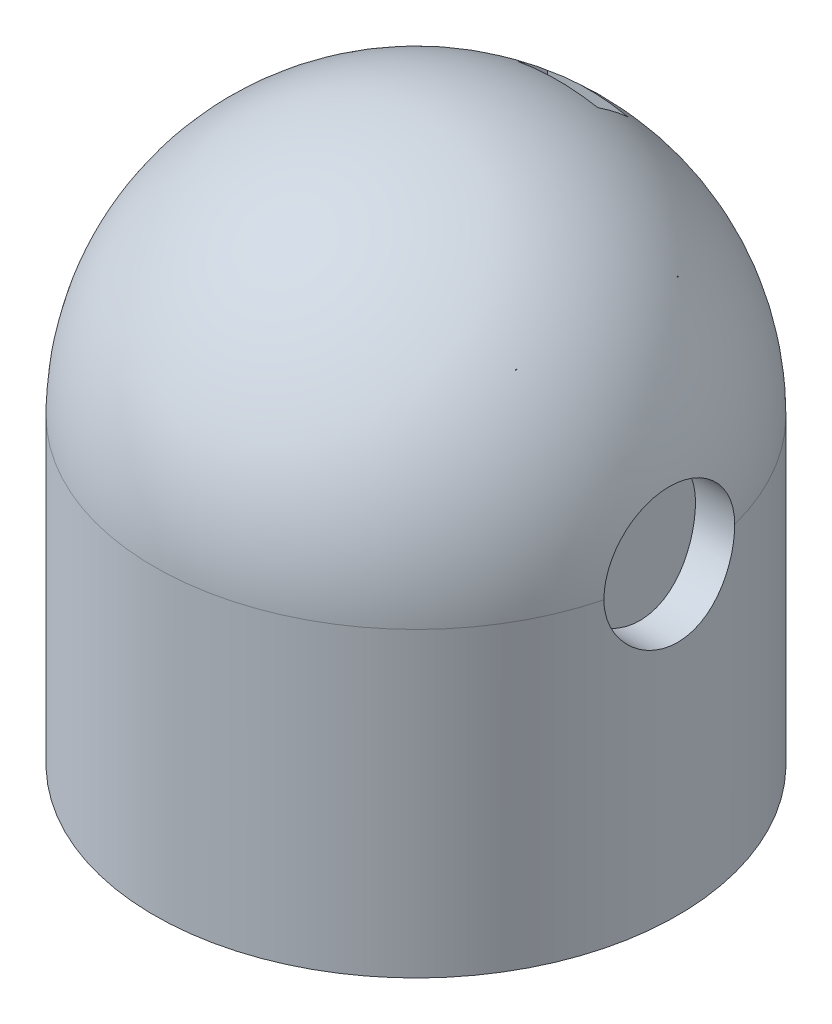
SolidWorks part; units mm, degrees
ref_plane "Front Plane" through (0, 0, 0) normal (0, 0, 1) x (1, 0, 0)
ref_plane "Top Plane" through (0, 0, 0) normal (0, 1, 0) x (1, 0, 0)
ref_plane "Right Plane" through (0, 0, 0) normal (1, 0, 0) x (0, 0, -1)
sketch "Sketch2" plane through (0, 0, 0) normal (0, 1, 0) x (1, 0, 0)
  line L0 (-33.02, 0) -> (33.02, 0) construction
  line L1 (-33.02, 0) -> (33.02, 0)
  arc A0 (33.02, 0) -> (-33.02, 0) centre (0, 0) ccw
  dimension "D1" = 66.04
revolve "Revolve1" add sketch "Sketch2" angle 180 about L0
sketch "Sketch3" plane through (0, 0, 0) normal (0, -1, 0) x (1, 0, 0)
  circle A0 centre (0, 0) radius 33.02
  circle A1 centre (0, 0) radius 33.02 construction
extrude "Boss-Extrude1" add sketch "Sketch3" along normal blind 38.1
shell "Shell1" thickness 4.7625
sketch "Sketch4" plane through (0, 0, 0) normal (1, 0, 0) x (0, 0, -1)
  circle A0 centre (0, 0) radius 8.255
  dimension "D1" = 16.51
extrude "Cut-Extrude1" cut sketch "Sketch4" against normal through all both and the other way through all
sketch "Sketch5" plane through (0, 0, 0) normal (0, 1, 0) x (1, 0, 0)
  line L1 (-18.14, -10.25) -> (22.86, -10.25)
  line L2 (-18.14, -10.25) -> (-18.14, 10.25)
  line L3 (-18.14, 10.25) -> (22.86, 10.25)
  line L4 (22.86, -10.25) -> (22.86, 10.25)
  line L9 (-20.68, 15.33) -> (25.4, 15.33)
  line L12 (-20.68, 15.33) -> (-20.68, -15.33)
  line L13 (-20.68, -15.33) -> (25.4, -15.33)
  line L14 (25.4, 15.33) -> (25.4, -15.33)
  point P4 (-18.14, 0)
  point P11 (2.36, -15.33)
  point P12 (2.36, -10.25)
  point P13 (22.86, 0)
  point P14 (25.4, 0)
  dimension "D1" = 20.5
  dimension "D2" = 41
  dimension "D3" = 22.86
  dimension "D5" = 5.08
  dimension "D4" = 2.54
extrude "Boss-Extrude4" add sketch "Sketch5" along normal up to surface and the other way blind 19.05 up to face at (0, 4.1275, 0)
ref_plane "Plane1" through (0, 21.59, 0) normal (0, 1, 0) x (1, 0, 0)
sketch "Sketch8" plane through (0, 21.59, 0) normal (0, 1, 0) x (1, 0, 0)
  line L0 (-18.14, 10.25) -> (15.0763, 10.25)
  line L4 (-18.14, 10.25) -> (-18.14, -10.25)
  line L5 (15.0763, 10.25) -> (15.0763, -10.25)
  line L6 (15.0763, -10.25) -> (-18.14, -10.25)
  line L7 (-18.14, 10.25) -> (22.86, 10.25) construction
  line L8 (22.86, -10.25) -> (-18.14, -10.25) construction
extrude "Boss-Extrude6" add sketch "Sketch8" along normal up to surface up to face at (3.092, 22.5961, 0)
sketch "Sketch9" plane through (0, 21.59, 0) normal (0, -1, 0) x (1, 0, 0)
  line L1 (-9.885, 10.25) -> (-4.805, 10.25)
  line L2 (-9.885, 10.25) -> (-9.885, -10.25)
  line L3 (-9.885, -10.25) -> (-4.805, -10.25)
  line L4 (-4.805, 10.25) -> (-4.805, -10.25)
  line L8 (-18.14, 10.25) -> (22.86, 10.25) construction
  line L9 (22.86, -10.25) -> (-18.14, -10.25) construction
  line L10 (-18.14, -10.25) -> (-18.14, 10.25) construction
  point P10 (-7.345, -10.25)
  dimension "D1" = 5.08
  dimension "D2" = 10.795
extrude "Cut-Extrude2" cut sketch "Sketch9" against normal blind 7.5
sketch "Sketch12" plane through (0, 21.59, 0) normal (0, -1, 0) x (1, 0, 0)
  line L1 (15.0763, 10.25) -> (22.86, 10.25)
  line L2 (15.0763, 10.25) -> (15.0763, -10.25)
  line L3 (15.0763, -10.25) -> (22.86, -10.25)
  line L4 (22.86, 10.25) -> (22.86, -10.25)
sketch "Sketch15" plane through (0, 21.59, 0) normal (0, -1, 0) x (1, 0, 0)
  line L1 (-15.0763, 10.25) -> (-18.14, 10.25)
  line L2 (-15.0763, 10.25) -> (-15.0763, -10.25)
  line L3 (-15.0763, -10.25) -> (-18.14, -10.25)
  line L4 (-18.14, 10.25) -> (-18.14, -10.25)
  line L5 (22.86, 10.25) -> (15.0763, 10.25)
  line L6 (22.86, 10.25) -> (22.86, -10.25)
  line L7 (22.86, -10.25) -> (15.0763, -10.25)
  line L8 (15.0763, 10.25) -> (15.0763, -10.25)
extrude "Cut-Extrude5" cut sketch "Sketch15" along normal through all
sketch "Sketch10" plane through (0, -19.05, 0) normal (0, -1, 0) x (1, 0, 0)
  line L1 (-5.08, -17.87) -> (5.08, -17.87)
  line L2 (-5.08, -17.87) -> (-5.08, -21.68)
  line L3 (-5.08, -21.68) -> (5.08, -21.68)
  line L4 (5.08, -17.87) -> (5.08, -21.68)
  line L7 (23.7377, -15.33) -> (-20.68, -15.33) construction
  point P6 (0, -17.87)
  dimension "D1" = 3.81
  dimension "D2" = 10.16
  dimension "D3" = 2.54
extrude "Cut-Extrude3" cut sketch "Sketch10" against normal through all
sketch "Sketch11" plane through (0, -19.05, 0) normal (0, -1, 0) x (1, 0, 0)
  line L6 (-18.14, -10.25) -> (-18.14, 10.25) construction
  line L7 (-18.14, 6.35) -> (-25.76, 6.35)
  line L8 (-18.14, 6.35) -> (-18.14, -6.35)
  line L9 (-18.14, -6.35) -> (-25.76, -6.35)
  line L10 (-25.76, 6.35) -> (-25.76, -6.35)
  point P6 (-18.14, 0)
  dimension "D1" = 12.7
  dimension "D2" = 7.62
extrude "Cut-Extrude4" cut sketch "Sketch11" against normal blind 36.83
sketch "Sketch16" plane through (0, -19.05, 0) normal (0, -1, 0) x (-1, 0, 0)
  line L0 (-23.7377, 15.33) -> (20.68, 15.33) construction
  line L1 (2.54, 10.25) -> (-2.54, 10.25)
  line L2 (2.54, 10.25) -> (2.54, 15.33)
  line L3 (2.54, 15.33) -> (-2.54, 15.33)
  line L4 (-2.54, 10.25) -> (-2.54, 15.33)
  line L5 (18.14, 10.25) -> (-15.0763, 10.25) construction
  point P7 (0, 10.25)
  dimension "D1" = 5.08
extrude "Cut-Extrude6" cut sketch "Sketch16" against normal up to surface (40.64 mm away) up to face at (5.1357, 21.59, 0)
sketch "Sketch17" plane through (0, 21.59, 0) normal (0, -1, 0) x (1, 0, 0)
  line L1 (20.32, 3.175) -> (-2.54, 3.175)
  line L2 (20.32, 3.175) -> (20.32, -3.175)
  line L3 (20.32, -3.175) -> (-2.54, -3.175)
  line L4 (-2.54, 3.175) -> (-2.54, -3.175)
  line L5 (-2.54, -10.25) -> (-2.54, -15.33) construction
  line L6 (22.86, 10.25) -> (22.86, -10.25) construction
  point P6 (-2.54, 0)
  dimension "D1" = 6.35
  dimension "D2" = 2.54
extrude "Cut-Extrude7" cut sketch "Sketch17" against normal blind 3.81
sketch "Sketch18" plane through (0, 21.59, 0) normal (0, -1, 0) x (1, 0, 0)
  line L1 (-2.54, -3.175) -> (2.54, -3.175)
  line L2 (-2.54, -3.175) -> (-2.54, -15.33)
  line L3 (-2.54, -15.33) -> (2.54, -15.33)
  line L4 (2.54, -3.175) -> (2.54, -15.33)
extrude "Cut-Extrude8" cut sketch "Sketch18" against normal blind 3.81
fillet "Fillet1" radius 5.08 2 edges at (-2.54, 23.495, 3.175) (2.54, 23.495, -3.175)
